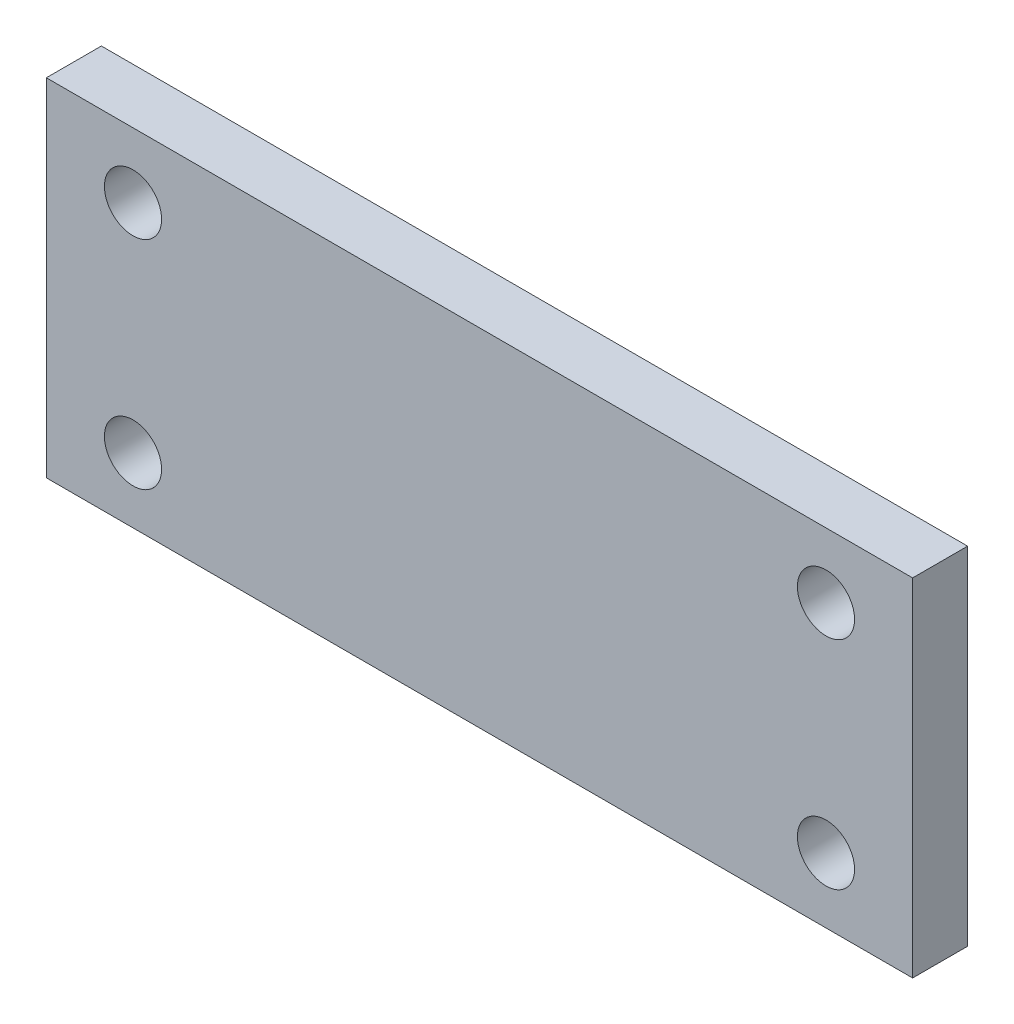
SolidWorks part; units mm, degrees
ref_plane "Front Plane" through (0, 0, 0) normal (0, 0, 1) x (1, 0, 0)
ref_plane "Top Plane" through (0, 0, 0) normal (0, 1, 0) x (1, 0, 0)
ref_plane "Right Plane" through (0, 0, 0) normal (1, 0, 0) x (0, 0, -1)
sketch "Sketch1" plane through (0, 0, 0) normal (0, 0, 1) x (1, 0, 0)
  line L0 (-40, 20) -> (-40, -20) construction
  line L1 (50, -20) -> (-50, -20)
  line L2 (50, -20) -> (50, 20)
  line L3 (50, 20) -> (-50, 20)
  line L4 (-50, -20) -> (-50, 20)
  line L5 (50, -20) -> (-50, 20) construction
  line L6 (50, 20) -> (-50, -20) construction
  line L7 (-40, 0) -> (-50, 0) construction
  line L8 (0, 20) -> (0, -20) construction
  line L9 (40, 0) -> (50, 0) construction
  line L10 (40, 20) -> (40, -20) construction
  circle A0 centre (-40, 12.5) radius 3.3
  circle A1 centre (-40, -12.5) radius 3.3
  circle A2 centre (40, -12.5) radius 3.3
  circle A3 centre (40, 12.5) radius 3.3
  point P0 (0, 0)
  dimension "D5" = 6.6
  dimension "D1" = 40
  dimension "D2" = 100
  dimension "D3" = 10
  dimension "D4" = 25
extrude "Boss-Extrude1" add sketch "Sketch1" along normal mid plane 6.35
